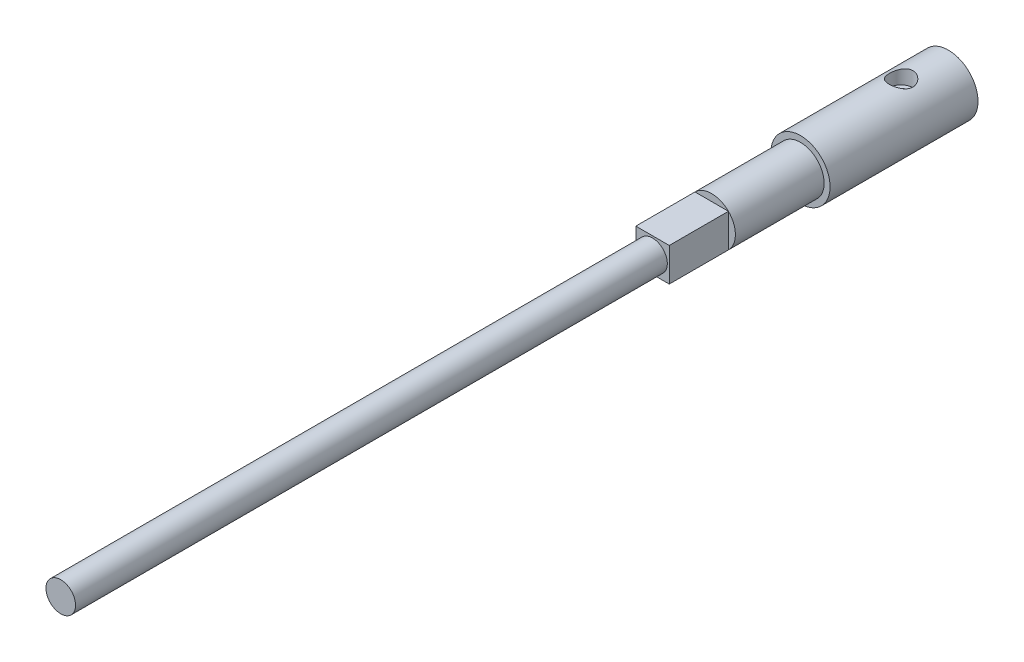
SolidWorks part; units mm, degrees
material "AISI 1020"
ref_plane "Front" through (0, 0, 0) normal (0, 0, 1) x (1, 0, 0)
ref_plane "Top" through (0, 0, 0) normal (0, 1, 0) x (1, 0, 0)
ref_plane "Right" through (0, 0, 0) normal (1, 0, 0) x (0, 0, -1)
sketch "Croquis1" plane through (0, 0, 0) normal (0, 0, 1) x (1, 0, 0)
  circle A0 centre (0, 0) radius 5
  dimension "D1" = 10
extrude "Saliente-Extruir1" add sketch "Croquis1" along normal mid plane 25
sketch "Croquis2" plane through (0, 0, -12.5) normal (0, 0, -1) x (-1, 0, 0)
  circle A0 centre (0, 0) radius 2
  dimension "D1" = 4
extrude "Cortar-Extruir1" cut sketch "Croquis2" against normal blind 15.5
ref_plane "Plano1" through (0, 5, 0) normal (0, 1, 0) x (1, 0, 0)
sketch "Croquis3" plane through (0, 5, 0) normal (0, 1, 0) x (1, 0, 0)
  line L0 (0, -5.5) -> (0, 5.5) construction
  line L1 (5, 12.5) -> (-5, 12.5) construction
  circle A0 centre (0, 4.5) radius 2
  dimension "D1" = 4
  dimension "D2" = 8
extrude "Cortar-Extruir2" cut sketch "Croquis3" against normal blind 2.5
sketch "Croquis4" plane through (0, 0, 12.5) normal (0, 0, 1) x (1, 0, 0)
  circle A0 centre (0, 0) radius 4
  dimension "D1" = 8
extrude "Saliente-Extruir2" add sketch "Croquis4" along normal blind 15
sketch "Croquis5" plane through (0, 0, 27.5) normal (0, 0, 1) x (1, 0, 0)
  line L1 (-2.8284, -2.8284) -> (2.8284, -2.8284)
  line L2 (-2.8284, -2.8284) -> (-2.8284, 2.8284)
  line L3 (-2.8284, 2.8284) -> (2.8284, 2.8284)
  line L4 (2.8284, -2.8284) -> (2.8284, 2.8284)
  line L5 (-2.8284, -2.8284) -> (2.8284, 2.8284) construction
  line L6 (-2.8284, 2.8284) -> (2.8284, -2.8284) construction
  circle A0 centre (0, 0) radius 4 construction
  point P0 (0, 0)
extrude "Saliente-Extruir3" add sketch "Croquis5" along normal blind 10
sketch "Croquis6" plane through (0, 2.5, 0) normal (0, 1, 0) x (1, 0, 0)
  line L0 (0, -5.5) -> (0, 5.5) construction
  line L1 (5, 12.5) -> (-5, 12.5) construction
  circle A0 centre (0, 4.5) radius 1.265
  dimension "D1" = 2.53
  dimension "D2" = 8
extrude "Cortar-Extruir3" cut sketch "Croquis6" against normal up to next
ref_plane "Plano2" through (0, -5, 0) normal (0, -1, 0) x (-1, 0, 0)
sketch "Croquis7" plane through (0, -5, 0) normal (0, -1, 0) x (-1, 0, 0)
  line L1 (-2, -5) -> (2, -5)
  line L2 (-2, -5) -> (-2, 5)
  line L3 (-2, 5) -> (2, 5)
  line L4 (2, -5) -> (2, 5)
  line L5 (-2, -5) -> (2, 5) construction
  line L6 (-2, 5) -> (2, -5) construction
  point P0 (0, 0)
  dimension "D1" = 10
  dimension "D2" = 4
extrude "Cortar-Extruir4" cut sketch "Croquis7" against normal blind 2
sketch "Croquis8" plane through (0, 0, 37.5) normal (0, 0, 1) x (1, 0, 0)
  circle A0 centre (0, 0) radius 2.5
  dimension "D1" = 5
extrude "Saliente-Extruir4" add sketch "Croquis8" along normal blind 100
